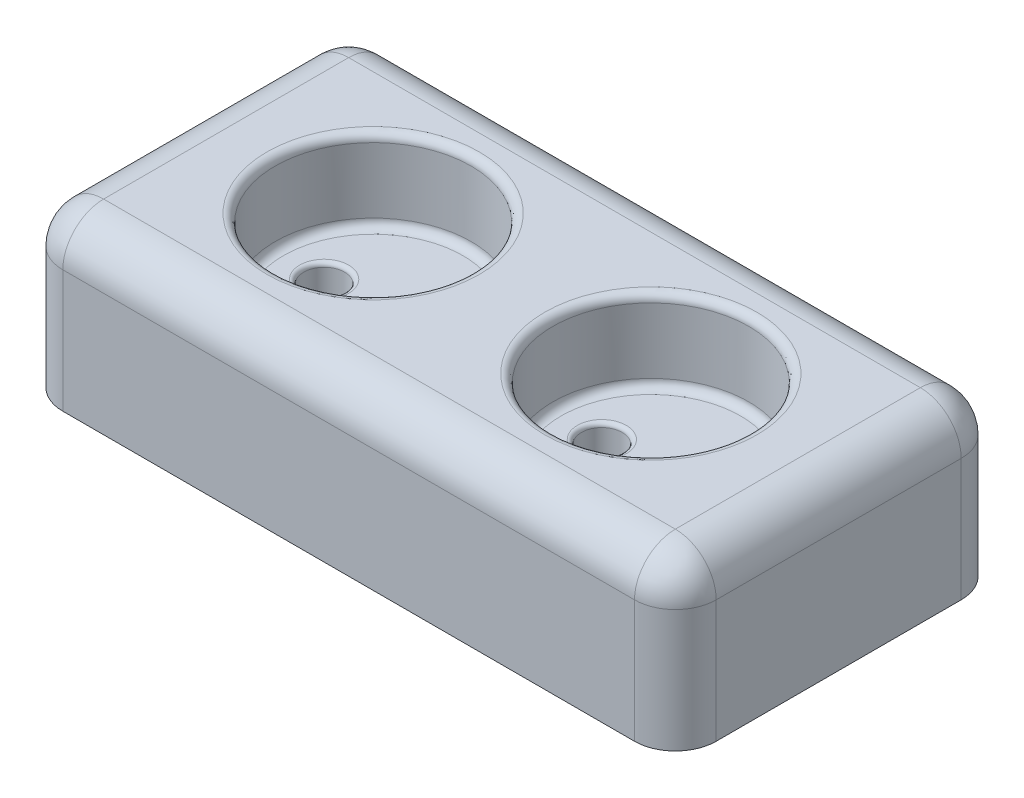
SolidWorks part; units mm, degrees
ref_plane "정면" through (0, 0, 0) normal (0, 0, 1) x (1, 0, 0)
ref_plane "윗면" through (0, 0, 0) normal (0, 1, 0) x (1, 0, 0)
ref_plane "우측면" through (0, 0, 0) normal (1, 0, 0) x (0, 0, -1)
sketch "스케치1" plane through (0, 0, 0) normal (0, 1, 0) x (1, 0, 0)
  line L1 (-50.1994, -29.1829) -> (29.8006, -29.1829)
  line L2 (-50.1994, -29.1829) -> (-50.1994, 10.8171)
  line L3 (-50.1994, 10.8171) -> (29.8006, 10.8171)
  line L4 (29.8006, -29.1829) -> (29.8006, 10.8171)
  dimension "D1" = 40
  dimension "D2" = 80
extrude "보스-돌출1" add sketch "스케치1" along normal blind 20
sketch "스케치3" plane through (0, 20, 0) normal (0, 1, 0) x (1, 0, 0)
  line L0 (-50.1994, -9.1829) -> (29.8006, -9.1829) construction
  line L1 (-50.1994, 10.8171) -> (-50.1994, -29.1829) construction
  line L2 (29.8006, -29.1829) -> (29.8006, 10.8171) construction
  circle A0 centre (-27.1994, -9.1829) radius 12
  circle A1 centre (6.8006, -9.1829) radius 12
  point P10 (-33.9755, -9.1829)
  point P11 (14.7447, -9.1829)
  point P12 (0, 0)
  point P13 (0, 0)
  point P14 (0, 0)
  dimension "D1" = 24
  dimension "D2" = 24
  dimension "D3" = 23
  dimension "D4" = 23
extrude "컷-돌출1" cut sketch "스케치3" against normal blind 10 contours A1 | A0
sketch "스케치4" plane through (0, 10, 0) normal (0, 1, 0) x (1, 0, 0)
  line L0 (-39.1994, -9.1829) -> (-27.1994, -9.1829) construction
  line L1 (-15.1994, -9.1829) -> (-27.1994, -9.1829) construction
  circle A0 centre (-27.1994, -9.1829) radius 12 construction
  circle A1 centre (-27.1994, -9.1829) radius 12 construction
sketch "스케치5" plane through (0, 10, 0) normal (0, 1, 0) x (1, 0, 0)
  line L0 (-5.1994, -9.1829) -> (6.8006, -9.1829) construction
  line L1 (6.8006, -9.1829) -> (18.8006, -9.1829) construction
  line L2 (-39.1994, -9.1829) -> (-27.1994, -9.1829) construction
  line L3 (-15.1994, -9.1829) -> (-27.1994, -9.1829) construction
  circle A0 centre (6.8006, -9.1829) radius 12 construction
  circle A1 centre (6.8006, -9.1829) radius 12 construction
  circle A2 centre (-33.1994, -9.1829) radius 2.5
  circle A3 centre (-21.1994, -9.1829) radius 2.5
  circle A4 centre (0.8006, -9.1829) radius 2.5
  circle A5 centre (12.8006, -9.1829) radius 2.5
  dimension "D1" = 5
  dimension "D2" = 5
  dimension "D3" = 5
  dimension "D4" = 5
extrude "컷-돌출2" cut sketch "스케치5" against normal through all
fillet "필렛1" radius 5 4 edges at (-50.1994, 10, -10.8171) (29.8006, 10, -10.8171) (29.8006, 10, 29.1829) (-50.1994, 10, 29.1829)
fillet "필렛2" radius 5 8 edges at (-48.7349, 20, 27.7184) (-50.1994, 20, 9.1829) (-10.1994, 20, 29.1829) (28.3362, 20, 27.7184) (29.8006, 20, 9.1829) (-10.1994, 20, -10.8171) (-48.7349, 20, -9.3526) (28.3362, 20, -9.3526)
fillet "필렛3" radius 1 4 edges at (6.8006, 10, 21.1829) (6.8006, 20, 21.1829) (-27.1994, 20, 21.1829) (-27.1994, 10, 21.1829)
fillet "필렛4" radius 0.5 4 edges at (12.8006, 10, 11.6829) (0.8006, 10, 11.6829) (-21.1994, 10, 11.6829) (-33.1994, 10, 11.6829)
